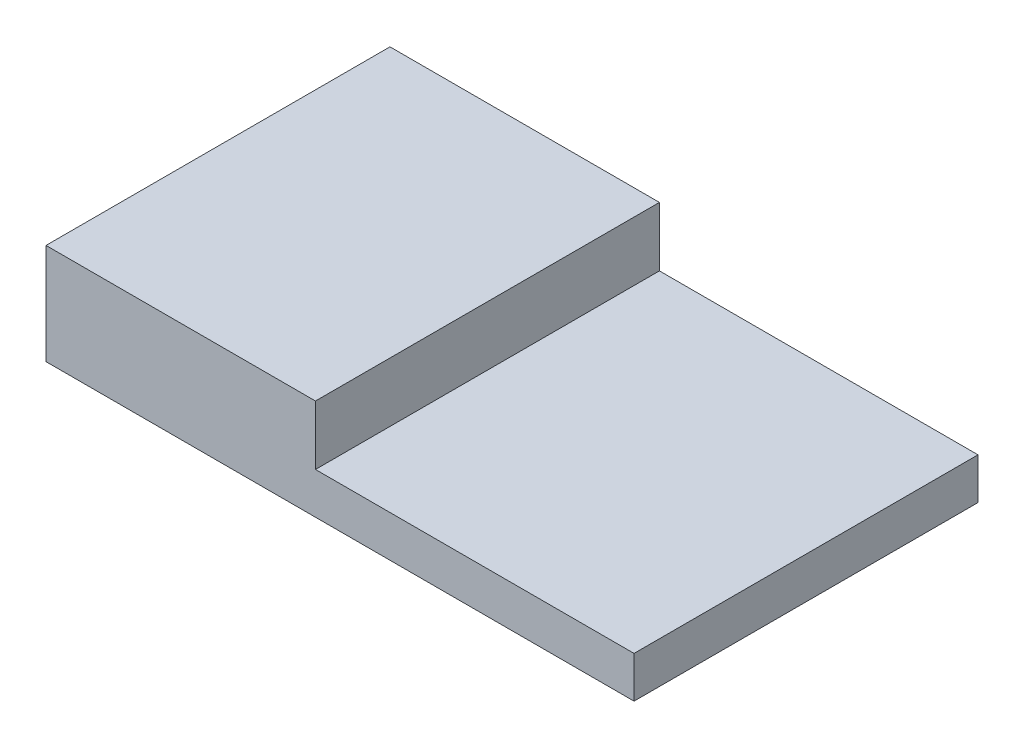
SolidWorks part; units mm, degrees
ref_plane "Front Plane" through (0, 0, 0) normal (0, 0, 1) x (1, 0, 0)
ref_plane "Top Plane" through (0, 0, 0) normal (0, 1, 0) x (1, 0, 0)
ref_plane "Right Plane" through (0, 0, 0) normal (1, 0, 0) x (0, 0, -1)
sketch "Sketch1" plane through (0, 0, 0) normal (0, 0, 1) x (1, 0, 0)
  line L0 (0, 18.5857) -> (0, 0)
  line L1 (0, 0) -> (108.5582, 0)
  line L2 (108.5582, 0) -> (108.5582, 7.638)
  line L3 (108.5582, 7.638) -> (49.7458, 7.638)
  line L4 (49.7458, 7.638) -> (49.7458, 18.5857)
  line L5 (49.7458, 18.5857) -> (0, 18.5857)
extrude "Extrude1" add sketch "Sketch1" against normal blind 63.5
